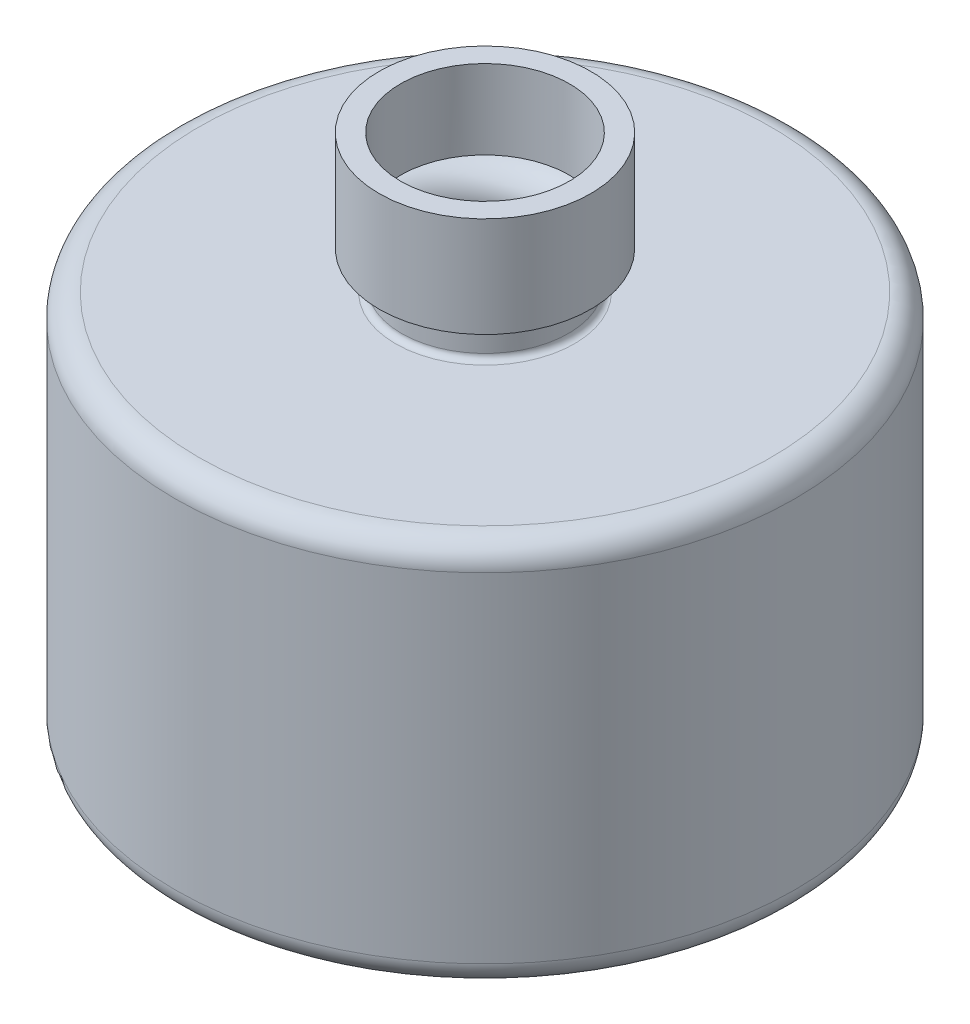
SolidWorks part; units mm, degrees
material "Glass"
ref_plane "Front Plane" through (0, 0, 0) normal (0, 0, 1) x (1, 0, 0)
ref_plane "Top Plane" through (0, 0, 0) normal (0, 1, 0) x (1, 0, 0)
ref_plane "Right Plane" through (0, 0, 0) normal (1, 0, 0) x (0, 0, -1)
sketch "Sketch1" plane through (0, 0, 0) normal (0, 0, 1) x (1, 0, 0)
  line L0 (0, 0) -> (-16.51, 0)
  line L1 (0, 0) -> (-16.51, 0) construction
  line L2 (0, 0) -> (0, 27.94) construction
  line L3 (0, 27.94) -> (-16.51, 27.94) construction
  line L4 (-16.51, 0) -> (-16.51, 27.94) construction
  line L5 (-16.51, 0) -> (-16.51, 20.574)
  line L6 (-16.51, 20.574) -> (-4.445, 20.574)
  line L7 (-4.445, 20.574) -> (-4.445, 22.606)
  line L8 (-4.445, 22.606) -> (-5.6388, 22.606)
  line L9 (-5.6388, 22.606) -> (-5.6388, 27.94)
  line L10 (-5.6388, 27.94) -> (0, 27.94)
  line L11 (0, 27.94) -> (0, 0)
  dimension "D1" = 16.51
  dimension "D2" = 5.334
  dimension "D3" = 20.574
  dimension "D4" = 2.032
  dimension "D5" = 5.6388
  dimension "D6" = 4.445
revolve "Revolve1" add sketch "Sketch1" angle 360 about L11
fillet "Fillet1" radius 1.27 2 edges at (0, 0, 16.51) (0, 20.574, 16.51)
fillet "Fillet2" radius 0.3175 1 edges at (0, 20.574, 4.445)
fillet "Fillet3" radius 0.3175 1 edges at (0, 22.606, 4.445)
shell "Shell1" thickness 1.143
